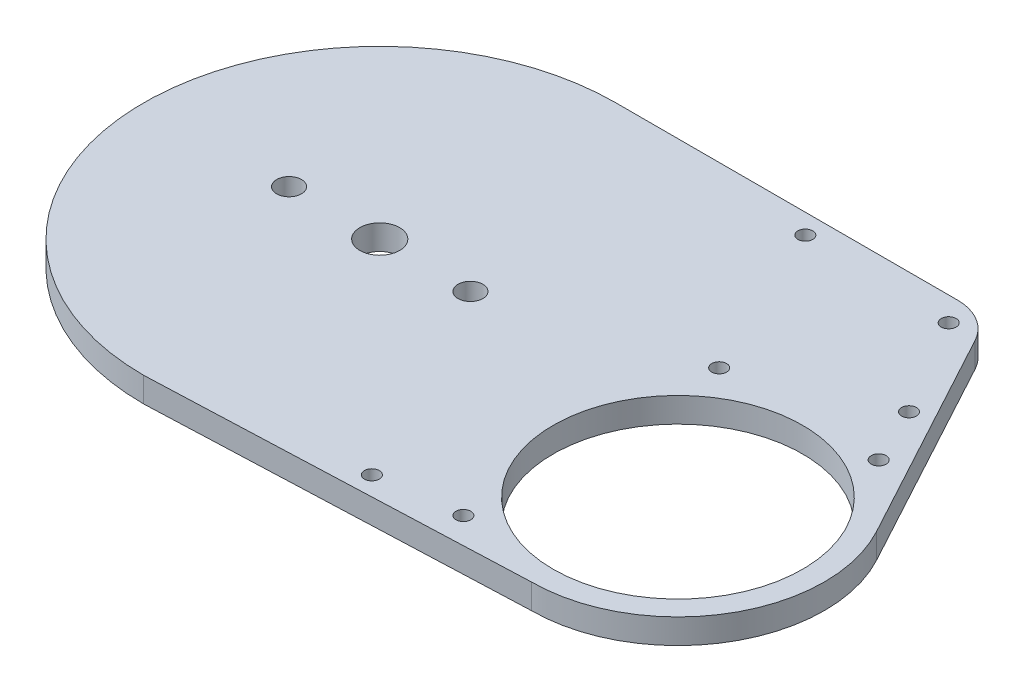
SolidWorks part; units mm, degrees
ref_plane "前视基准面" through (0, 0, 0) normal (0, 0, 1) x (1, 0, 0)
ref_plane "上视基准面" through (0, 0, 0) normal (0, 1, 0) x (1, 0, 0)
ref_plane "右视基准面" through (0, 0, 0) normal (1, 0, 0) x (0, 0, -1)
sketch "Sketch1" plane through (0, 0, 0) normal (0, 1, 0) x (1, 0, 0)
  line L0 (0, 0) -> (0, -15) construction
  line L1 (0, -15) -> (75, -15) construction
  line L2 (0, -47.5) -> (0, -44.5) construction
  line L3 (0, -44.5) -> (94.3585, -44.5) construction
  line L4 (0, -47.5) -> (75, -44.5)
  line L5 (0, 47.5) -> (68.764, 47.5)
  line L6 (77.559, 42.259) -> (100.9453, -0.9611)
  line L7 (68.764, 47.5) -> (77.559, 42.259) construction
  line L8 (73.8831, 46.0904) -> (71.8355, 42.6542) construction
  arc A0 (0, 47.5) -> (0, -47.5) centre (0, 0) ccw
  circle A1 centre (75, -15) radius 25.1
  arc A2 (75, -44.5) -> (100.9453, -0.9611) centre (75, -15) ccw
  circle A3 centre (75.0001, 47.5) radius 7.5 construction
  arc A4 (77.559, 42.259) -> (68.764, 47.5) centre (68.764, 37.5) ccw
  circle A5 centre (0, 0) radius 4
  circle A7 centre (88.688, 11.711) radius 1.5
  circle A8 centre (56.5917, 11.711) radius 1.5
  circle A9 centre (56.5917, -39.7686) radius 1.5
  circle A10 centre (0, 0) radius 18.25 construction
  circle A11 centre (18.25, 0) radius 2.5
  circle A12 centre (-18.25, 0) radius 2.5
  circle A13 centre (71.8355, 42.6542) radius 1.5
  circle A14 centre (42.1373, 43.5) radius 1.5
  circle A15 centre (83.3547, 23.1429) radius 1.5
  circle A16 centre (40.2934, -41.8851) radius 1.5
  dimension "D1" = 95
  dimension "D4" = 50.2
  dimension "D6" = 15
  dimension "D7" = 10
  dimension "D8" = 8
  dimension "D9" = 3
  dimension "D10" = 3
  dimension "D11" = 3
  dimension "D12" = 3
  dimension "D13" = 36.5
  dimension "D14" = 5
  dimension "D15" = 5
  dimension "D17" = 3
  dimension "D18" = 3
  dimension "D19" = 3
  dimension "D2" = 15
  dimension "D3" = 75
  dimension "D5" = 3
  dimension "D16" = 4
extrude "Boss-Extrude1" add sketch "Sketch1" along normal blind 5
